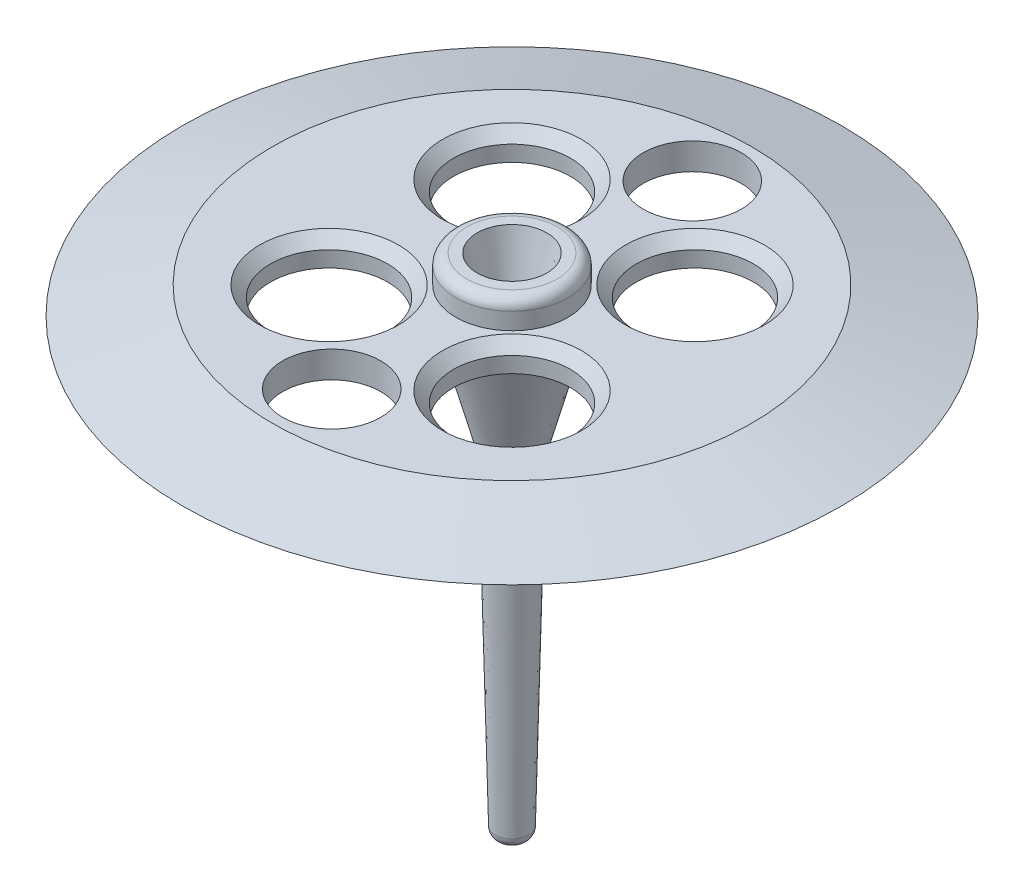
SolidWorks part; units mm, degrees
material "ABS"
ref_plane "Plan de face" through (0, 0, 0) normal (0, 0, 1) x (1, 0, 0)
ref_plane "Plan de dessus" through (0, 0, 0) normal (0, 1, 0) x (1, 0, 0)
ref_plane "Plan de droite" through (0, 0, 0) normal (1, 0, 0) x (0, 0, -1)
sketch "Esquisse1" plane through (0, 0, 0) normal (0, 0, 1) x (1, 0, 0)
  line L0 (0, 0) -> (0, 6.0605) construction
  line L1 (-5.15, 0) -> (-30.25, 0)
  line L2 (-30.25, 0) -> (-22, 2.45)
  line L3 (-22, 2.45) -> (-5.15, 2.45)
  line L4 (-5.15, 0) -> (-2.2311, -10.884)
  line L5 (-2.1972, -11.1201) -> (-1.5224, -40.5229)
  line L6 (-0.5227, -41.5) -> (0, -41.5)
  line L7 (0, -41.5) -> (0, 0)
  line L8 (-5.15, 2.45) -> (-5.15, 4)
  line L9 (-4.15, 5) -> (-3.197, 5)
  line L11 (-3.197, 5) -> (-2, 0)
  line L12 (-2, 0) -> (0, 0)
  arc A0 (-0.5227, -41.5) -> (-1.5224, -40.5229) centre (-0.5227, -40.5) cw
  arc A1 (-2.1972, -11.1201) -> (-2.2311, -10.884) centre (-3.197, -11.143) ccw
  arc A2 (-4.15, 5) -> (-5.15, 4) centre (-4.15, 4) ccw
  point P14 (-1.5, -41.5)
  point P17 (-2.2, -11)
  point P20 (-5.15, 4.95)
  dimension "D11" = 1
  dimension "D1" = 2.45
  dimension "D2" = 30.25
  dimension "D3" = 2.5
  dimension "D4" = 5.15
  dimension "D5" = 2.2
  dimension "D6" = 41.5
  dimension "D7" = 1.5
  dimension "D8" = 5
  dimension "D9" = 22
  dimension "D10" = 11
  dimension "D12" = 2
revolve "Révolution1" add sketch "Esquisse1" angle 360 about L0
sketch "Esquisse2" plane through (0, 2.45, 0) normal (0, 1, 0) x (1, 0, 0)
  line L0 (0, 0) -> (0, 24.6247) construction
  line L1 (0, 0) -> (-37.374, 0) construction
  line L2 (0, 0) -> (-8.3969, 8.3969) construction
  line L3 (0, 0) -> (8.3969, 8.3969) construction
  line L4 (0, 0) -> (-8.3969, -8.3969) construction
  line L5 (0, 0) -> (8.3969, -8.3969) construction
  circle A0 centre (0, 16.55) radius 4.5
  circle A1 centre (-8.3969, 8.3969) radius 5.375
  circle A2 centre (8.3969, 8.3969) radius 5.375
  circle A3 centre (8.3969, -8.3969) radius 5.375
  circle A4 centre (0, -16.55) radius 4.5
  circle A5 centre (-8.3969, -8.3969) radius 5.375
  circle A6 centre (0, 0) radius 11.875 construction
  dimension "D2" = 9
  dimension "D3" = 10.75
  dimension "D4" = 23.75
  dimension "D1" = 16.55
  dimension "D5" = 90
extrude "Enlèv. mat.-Extru.1" cut sketch "Esquisse2" against normal through all
chamfer "Chanfrein2" distance 1 angle 45 4 edges at (8.3969, 2.45, -13.7719) (8.3969, 2.45, 13.7719) (-8.3969, 2.45, 3.0219) (-8.3969, 2.45, -3.0219)
